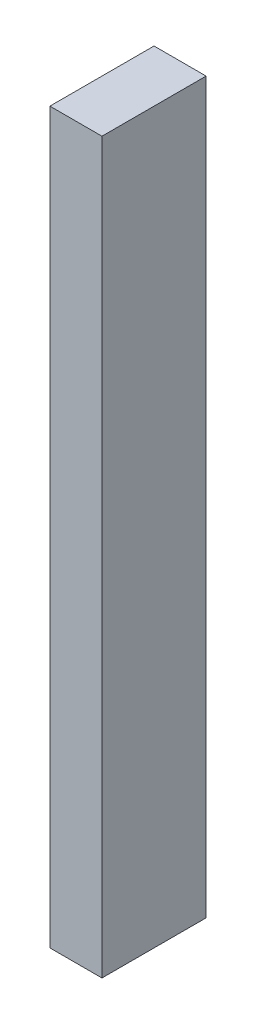
SolidWorks part; units mm, degrees
material "Teak"
ref_plane "Front Plane" through (0, 0, 0) normal (0, 0, 1) x (1, 0, 0)
ref_plane "Top Plane" through (0, 0, 0) normal (0, 1, 0) x (1, 0, 0)
ref_plane "Right Plane" through (0, 0, 0) normal (1, 0, 0) x (0, 0, -1)
sketch "Sketch1" plane through (0, 0, 0) normal (0, 1, 0) x (1, 0, 0)
  line L1 (0, 0) -> (50.8, 0)
  line L2 (0, 0) -> (0, 101.6)
  line L3 (0, 101.6) -> (50.8, 101.6)
  line L4 (50.8, 0) -> (50.8, 101.6)
  dimension "D1" = 101.6
  dimension "D2" = 50.8
extrude "Boss-Extrude1" add sketch "Sketch1" along normal blind 711.2
